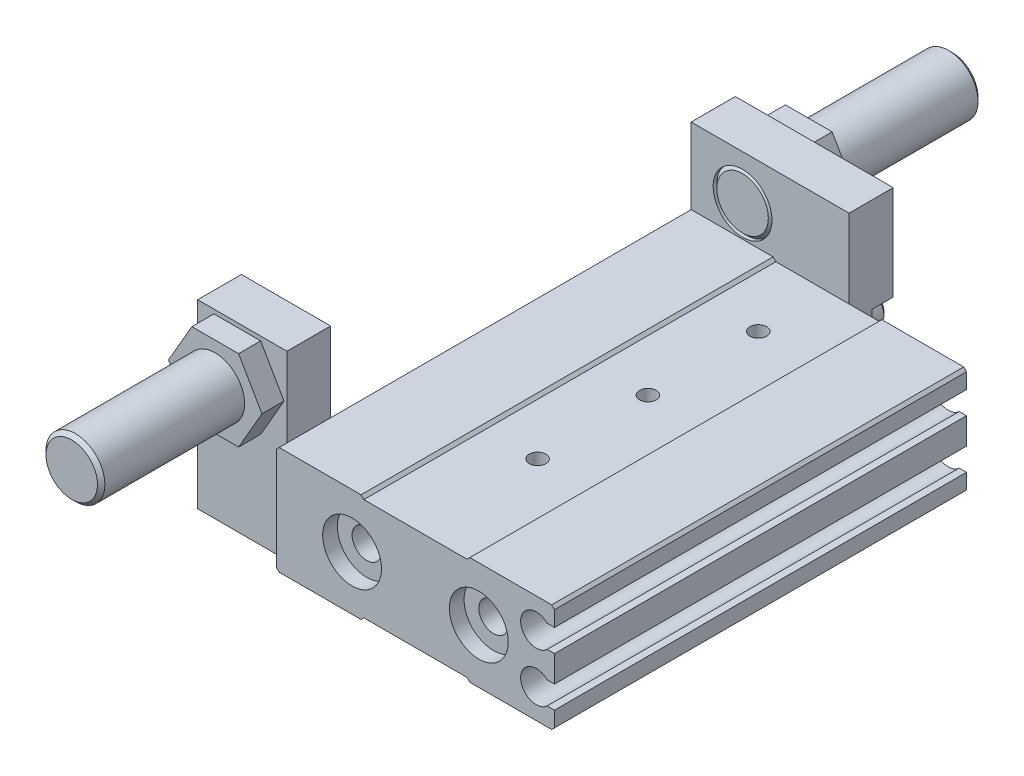
SolidWorks part; units mm, degrees
ref_plane "Front" through (0, 0, 0) normal (0, 0, 1) x (1, 0, 0)
ref_plane "Top" through (0, 0, 0) normal (0, 1, 0) x (1, 0, 0)
ref_plane "Right" through (0, 0, 0) normal (1, 0, 0) x (0, 0, -1)
ref_plane "Plane4" through (0, 0, 0) normal (0, 0, 1) x (-1, 0, 0)
sketch "Sketch1" plane through (0, 0, 57.45) normal (0, 0, 1) x (-1, 0, 0)
  line L0 (18.519, 7.3406) -> (18.9, 6.9596)
  line L1 (-7.0104, 6.9596) -> (7.0104, 6.9596)
  line L2 (18.519, 7.3406) -> (7.3914, 7.3406)
  line L3 (-7.3914, 7.3406) -> (-18.519, 7.3406)
  line L4 (7.0104, 6.9596) -> (7.3914, 7.3406)
  line L5 (-7.0104, 6.9596) -> (-7.3914, 7.3406)
  line L6 (-18.9, 6.9596) -> (-18.9, 4.8641)
  line L7 (-18.9, -6.9596) -> (-18.519, -7.3406)
  line L8 (-7.0104, -6.9596) -> (-7.3914, -7.3406)
  line L9 (-18.9, 1.7907) -> (-18.9, -1.7907)
  line L10 (-18.9, -4.8641) -> (-18.9, -6.9596)
  line L11 (-18.9, 6.9596) -> (-18.519, 7.3406)
  line L12 (18.9, 6.9596) -> (18.9, -6.9596)
  line L14 (-50, 0) -> (50, 0) construction
  line L15 (-7.3914, -7.3406) -> (-18.519, -7.3406)
  line L16 (-17.9137, -4.8641) -> (-18.9, -4.8641)
  line L17 (-14.3, 7.3406) -> (-14.3, 3.3274) construction
  line L18 (-7.0104, -6.9596) -> (7.0104, -6.9596)
  line L19 (7.0104, -6.9596) -> (7.3914, -7.3406)
  line L20 (18.9, -6.9596) -> (18.519, -7.3406)
  line L22 (-18.9, 0) -> (18.9, 0) construction
  line L23 (0, 0) -> (0, 6.9596) construction
  line L26 (18.519, -7.3406) -> (7.3914, -7.3406)
  line L27 (-17.9137, -1.7907) -> (-18.9, -1.7907)
  line L28 (-17.9137, 1.7907) -> (-18.9, 1.7907)
  line L29 (-17.9137, 4.8641) -> (-18.9, 4.8641)
  arc A0 (-17.9137, 1.7907) -> (-17.9137, 4.8641) centre (-16.4336, 3.3274) ccw
  arc A1 (-17.9137, -4.8641) -> (-17.9137, -1.7907) centre (-16.4336, -3.3274) ccw
  dimension "D5" = 4.2672
  dimension "D1" = 14.6812
  dimension "D2" = 45
  dimension "D3" = 0.381
  dimension "D4" = 4.6
  dimension "D6" = 14.0208
  dimension "D7" = 6.6548
  dimension "D8" = 3.0734
extrude "Base-Extrude" add sketch "Sketch1" along normal up to surface (56 mm away)
ref_plane "Plane8" through (0, 0, 55.45) normal (0, 0, 1) x (1, 0, 0)
sketch "Sketch2" plane through (0, 0, 57.45) normal (0, 0, -1) x (-1, 0, 0)
  line L0 (28.0615, 0) -> (-28.0615, 0) construction
  line L5 (0, 6.9596) -> (0, -6.9596) construction
  line L6 (7.0104, 6.9596) -> (-7.0104, 6.9596) construction
  line L7 (-7.0104, -6.9596) -> (7.0104, -6.9596) construction
  circle A0 centre (-8.6106, 0) radius 4
  circle A1 centre (8.6106, 0) radius 4
  dimension "D1" = 8
  dimension "D2" = 17.2212
extrude "Cut-Extrude1" cut sketch "Sketch2" along normal up to surface (54.7 mm away)
sketch "Sketch4" plane through (0, 0, 55.45) normal (0, 0, 1) x (1, 0, 0)
  circle A2 centre (8.6106, 0) radius 4 construction
  circle A3 centre (-8.6106, 0) radius 4 construction
  circle A4 centre (8.6106, 0) radius 4
  circle A5 centre (-8.6106, 0) radius 4
extrude "Boss-Extrude1" add sketch "Sketch4" against normal blind 10
sketch "Sketch19" plane through (0, 0, 55.45) normal (0, 0, 1) x (1, 0, 0)
  circle A0 centre (8.6106, 0) radius 2
  circle A1 centre (-8.6106, 0) radius 2
  circle A2 centre (-8.6106, 0) radius 4 construction
  circle A3 centre (8.6106, 0) radius 4 construction
  dimension "D1" = 4
extrude "Cut-Extrude3" cut sketch "Sketch19" against normal up to next
hole_wizard "#4-40 Tapped Hole2" positions "Sketch21" profile "Sketch20" tap size "#4-40" standard "Ansi Inch" end condition through all
sketch "Sketch21" plane through (0, -6.9596, 0) normal (0, -1, 0) x (1, 0, 0)
  point P0 (0, 40.85)
  point P1 (0, 25.85)
  point P2 (0, 10.85)
sketch "Sketch20" plane through (0, -6.9596, 40.85) normal (1, 0, 0) x (0, 0, -1)
  line L0 (0, 0) -> (0, 14.3002)
  line L1 (0, 14.3002) -> (1.1303, 14.3002)
  line L3 (1.1303, 14.3002) -> (1.1303, 5.6896)
  line L4 (1.1303, 5.6896) -> (1.4224, 5.6896)
  line L5 (1.4224, 5.6896) -> (1.4224, 0)
  line L7 (1.4224, 0) -> (0, 0)
  line L11 (0, -6.35) -> (0, 107.95) construction
  dimension "Thru Tap Drill Dia." = 2.2606
  dimension "Thru Tap Drill Depth" = 14.3002
  dimension "Thread Major Dia." = 2.8448
  dimension "Thread Depth" = 5.6896
hole_wizard "#3-48 Tapped Hole1" positions "Sketch23" profile "Sketch22" tap size "#3-56" standard "Ansi Inch"
sketch "Sketch23" plane through (0, 0, 1.45) normal (0, 0, -1) x (-1, 0, 0)
  line L0 (7.3914, -7.3406) -> (18.519, -7.3406) construction
  point P0 (16, -4.6406)
  point P1 (16, 4.3594)
  point P2 (-0.002, -4.6406)
  point P3 (-0.002, 2.3594)
  dimension "D1" = 2.7
  dimension "D2" = 9
  dimension "D3" = 16.002
  dimension "D4" = 16
  dimension "D5" = 7
sketch "Sketch22" plane through (-16, -4.6406, 1.45) normal (1, 0, 0) x (0, 1, 0)
  line L0 (0, 0) -> (0, 7.9282)
  line L1 (0, 7.9282) -> (1.0414, 7.3025)
  line L2 (1.0414, 7.3025) -> (1.0414, 5.0292)
  line L3 (1.0414, 5.0292) -> (1.2573, 5.0292)
  line L4 (1.2573, 5.0292) -> (1.2573, 0)
  line L5 (1.2573, 0) -> (0, 0)
  line L10 (0, 7.9282) -> (-1.0414, 7.3025) construction
  line L11 (0, -6.35) -> (0, 107.95) construction
  dimension "Tap Drill Dia." = 2.0828
  dimension "Tap Drill Depth" = 7.3025
  dimension "Thread Dia." = 2.5146
  dimension "Thread Depth" = 5.0292
  dimension "Drill Angle" = 118
hole_wizard "Hole1" positions "Sketch25" profile "Sketch24" legacy
sketch "Sketch25" plane through (0, -7.3406, 0) normal (0, -1, 0) x (1, 0, 0)
  point P0 (-14, 42.15)
sketch "Sketch24" plane through (-14, -7.3406, 42.15) normal (1, 0, 0) x (0, 0, -1)
  line L0 (0, 0) -> (0, 2.54)
  line L1 (0, 2.54) -> (1.5939, 2.54)
  line L2 (1.5939, 2.54) -> (1.5939, 0)
  line L3 (1.5939, 0) -> (0, 0)
  line L4 (0, 110) -> (0, -10) construction
  dimension "Diameter" = 3.1877
  dimension "Depth" = 2.54
sketch "Sketch27" plane through (0, -7.3406, 0) normal (0, -1, 0) x (1, 0, 0)
  line L0 (-18.9, 14.15) -> (-14, 14.15) construction
  line L1 (-18.9, 57.45) -> (-18.9, 1.45) construction
  line L2 (-18.9, 16.15) -> (-14, 16.15) construction
  line L3 (-18.9, 12.15) -> (-14, 12.15) construction
  line L4 (-15.5938, 14.5561) -> (-15.5938, 13.7438)
  line L5 (-12.4062, 14.5561) -> (-12.4062, 13.7438)
  arc A0 (-15.5938, 13.7438) -> (-12.4062, 13.7438) centre (-14, 13.7438) ccw
  arc A1 (-12.4062, 14.5561) -> (-15.5938, 14.5561) centre (-14, 14.5561) ccw
  dimension "D1" = 3.1877
  dimension "D2" = 4
extrude "Cut-Extrude4" cut sketch "Sketch27" against normal blind 2.5
hole_wizard "#10-32 Tapped Hole1" positions "Sketch29" profile "Sketch28" tap size "#10-32" standard "Ansi Inch"
sketch "Sketch29" plane through (-18.9, 0, 0) normal (-1, 0, 0) x (0, 0, 1)
  line L0 (57.45, 6.9596) -> (57.45, -6.9596) construction
  line L3 (1.45, -7.3406) -> (57.45, -7.3406) construction
  point P0 (44.95, -0.1406)
  dimension "D1" = 12.5
  dimension "D2" = 7.2
sketch "Sketch28" plane through (-18.9, -0.1406, 44.95) normal (0, 1, 0) x (0, 0, 1)
  line L0 (0, 0) -> (0, 13.2427)
  line L1 (0, 13.2427) -> (2.0193, 12.0294)
  line L2 (2.0193, 12.0294) -> (2.0193, 9.652)
  line L3 (2.0193, 9.652) -> (2.413, 9.652)
  line L4 (2.413, 9.652) -> (2.413, 0)
  line L5 (2.413, 0) -> (0, 0)
  line L10 (0, 13.2427) -> (-2.0193, 12.0294) construction
  line L11 (0, -6.35) -> (0, 107.95) construction
  dimension "Tap Drill Dia." = 4.0386
  dimension "Tap Drill Depth" = 12.0294
  dimension "Thread Major Dia." = 4.826
  dimension "Thread Depth" = 9.652
  dimension "Drill Angle" = 118
sketch "Sketch30" plane through (0, 0, 1.45) normal (0, 0, -1) x (-1, 0, 0)
  line L0 (-7.0104, -6.9596) -> (7.0104, -6.9596) construction
  line L1 (-2.941, 17.6514) -> (18.519, 17.6514)
  line L2 (-2.941, 17.6514) -> (-2.941, -6.5786)
  line L3 (-2.941, -6.5786) -> (18.519, -6.5786)
  line L4 (18.519, 17.6514) -> (18.519, -6.5786)
  line L5 (18.9, -6.9596) -> (18.9, 6.9596) construction
  dimension "D1" = 0.381
  dimension "D2" = 0.381
  dimension "D3" = 24.23
  dimension "D4" = 21.46
extrude "Boss-Extrude2" add sketch "Sketch30" along normal blind 6
sketch "Sketch31" plane through (0, 0, -4.55) normal (0, 0, -1) x (-1, 0, 0)
  line L0 (17.8899, 11.5714) -> (14.7144, 17.0714)
  line L1 (14.7144, 17.0714) -> (8.3636, 17.0714)
  line L2 (8.3636, 17.0714) -> (5.1881, 11.5714)
  line L3 (5.1881, 11.5714) -> (8.3636, 6.0714)
  line L4 (8.3636, 6.0714) -> (14.7144, 6.0714)
  line L5 (14.7144, 6.0714) -> (17.8899, 11.5714)
  line L6 (18.519, 17.6514) -> (-2.941, 17.6514) construction
  line L7 (18.519, -6.5786) -> (18.519, 17.6514) construction
  circle A0 centre (11.539, 11.5714) radius 6.3509 construction
  dimension "D1" = 6.08
  dimension "D2" = 6.98
  dimension "D3" = 11
sketch "Sketch48" plane through (0, 0, -4.55) normal (0, 0, -1) x (-1, 0, 0)
  line L0 (16, 6.7744) -> (18.519, 6.7744)
  line L1 (18.519, 6.7744) -> (18.519, 1.9444)
  line L2 (18.519, -6.5786) -> (18.519, 17.6514) construction
  line L3 (16, 1.9444) -> (18.519, 1.9444)
  line L4 (2.413, -4.6406) -> (2.413, -6.5786)
  line L5 (-2.941, -6.5786) -> (18.519, -6.5786) construction
  line L6 (2.413, -6.5786) -> (-2.941, -6.5786)
  line L7 (-0.002, -2.2256) -> (-2.941, -2.2256)
  line L8 (-2.941, 17.6514) -> (-2.941, -6.5786) construction
  line L9 (-2.941, -2.2256) -> (-2.941, -6.5786)
  line L10 (16, -2.2256) -> (18.519, -2.2256)
  line L11 (18.519, -2.2256) -> (18.519, -6.5786)
  line L12 (13.585, -4.6406) -> (13.585, -6.5786)
  line L13 (13.585, -6.5786) -> (18.519, -6.5786)
  line L14 (-0.002, 4.7744) -> (-2.941, 4.7744)
  line L15 (-0.002, -0.0556) -> (-2.941, -0.0556)
  line L16 (-2.941, -0.0556) -> (-2.941, 4.7744)
  arc A0 (16, 6.7744) -> (16, 1.9444) centre (16, 4.3594) ccw
  arc A1 (2.413, -4.6406) -> (-0.002, -2.2256) centre (-0.002, -4.6406) ccw
  arc A2 (16, -2.2256) -> (13.585, -4.6406) centre (16, -4.6406) ccw
  arc A3 (-0.002, -0.0556) -> (-0.002, 4.7744) centre (-0.002, 2.3594) ccw
  dimension "D1" = 2.415
extrude "Cut-Extrude9" cut sketch "Sketch48" against normal blind 2.87
extrude "Boss-Extrude3" add sketch "Sketch31" along normal blind 3
sketch "Sketch35" plane through (0, 0, -1.68) normal (0, 0, -1) x (-1, 0, 0)
  circle A0 centre (16, 4.3594) radius 2.032
  circle A1 centre (-0.002, 2.3594) radius 2.032
  circle A2 centre (-0.002, -4.6406) radius 2.032
  circle A3 centre (16, -4.6406) radius 2.032
  circle A4 centre (16, -4.6406) radius 1.2573 construction
  circle A7 centre (-0.002, 2.3594) radius 1.2573 construction
  circle A8 centre (-0.002, -4.6406) radius 1.2573 construction
  circle A9 centre (16, 4.3594) radius 1.2573 construction
  dimension "D1" = 4.064
extrude "Boss-Extrude5" add sketch "Sketch35" along normal blind 3
ref_plane "Plane9" through (0, 0, 49.95) normal (0, 0, 1) x (1, 0, 0)
sketch "Sketch36" plane through (0, 0, 49.95) normal (0, 0, 1) x (1, 0, 0)
  line L0 (-19.027, 17.6394) -> (-19.027, 5.3406)
  line L1 (-31.15, 17.6394) -> (-19.027, 17.6394)
  line L2 (-31.15, 17.6394) -> (-31.15, -6.9706)
  line L3 (-31.15, -6.9706) -> (-18.9, -6.9706)
  line L4 (-18.9, 5.3406) -> (-18.9, -6.9706)
  line L5 (-19.027, 5.3406) -> (-18.9, 5.3406)
  line L7 (-18.9, 17.6094) -> (-18.9, -5.8406) construction
  line L8 (-18.519, -7.3406) -> (-7.3914, -7.3406) construction
  line L11 (18.9, 7.3406) -> (-18.9, 7.3406) construction
  dimension "D1" = 12.25
  dimension "D2" = 0.127
  dimension "D3" = 24.61
  dimension "D4" = 0.37
  dimension "D5" = 2
extrude "Boss-Extrude6" add sketch "Sketch36" along normal blind 5.94
sketch "Sketch37" plane through (0, 0, 55.89) normal (0, 0, 1) x (1, 0, 0)
  line L0 (-31.15, 17.6394) -> (-31.15, -6.9706) construction
  line L1 (-22.5946, 17.0714) -> (-28.9454, 17.0714)
  line L2 (-28.9454, 17.0714) -> (-32.1209, 11.5714)
  line L3 (-32.1209, 11.5714) -> (-28.9454, 6.0714)
  line L4 (-28.9454, 6.0714) -> (-22.5946, 6.0714)
  line L5 (-22.5946, 6.0714) -> (-19.4191, 11.5714)
  line L6 (-8.3636, 6.0714) -> (-14.2967, 6.0714) construction
  line L8 (-19.4191, 11.5714) -> (-22.5946, 17.0714)
  circle A0 centre (-25.77, 11.5714) radius 5.5 construction
  dimension "D1" = 5.38
  dimension "D3" = 11
extrude "Boss-Extrude7" add sketch "Sketch37" along normal blind 3
sketch "Sketch38" plane through (0, 0, 58.89) normal (0, 0, 1) x (1, 0, 0)
  line L0 (-19.4191, 11.5714) -> (-22.5946, 17.0714) construction
  line L1 (-32.1209, 11.5714) -> (-28.9454, 6.0714) construction
  line L2 (-22.5946, 17.0714) -> (-28.9454, 17.0714) construction
  circle A0 centre (-25.77, 11.5714) radius 5.5 construction
  circle A1 centre (-25.77, 11.5714) radius 4
  dimension "D1" = 8
ref_plane "Plane11" through (0, 11.5714, 0) normal (0, 1, 0) x (-1, 0, 0)
extrude "Cut-Extrude7" cut sketch "Sketch38" against normal up to next
sketch "Sketch44" plane through (0, 11.5714, 0) normal (0, 1, 0) x (-1, 0, 0)
  line L0 (25.77, 58.89) -> (25.77, 49.95) construction
  line L1 (22.5946, 58.89) -> (28.9454, 58.89) construction
  line L2 (9.7125, 49.95) -> (-9.7125, 49.95) construction
  line L4 (25.77, 78.39) -> (29.77, 78.39)
  line L5 (25.77, 78.39) -> (25.77, 49.95)
  line L6 (25.77, 49.95) -> (29.27, 49.95)
  line L7 (29.77, 78.39) -> (29.77, 50.45)
  line L8 (29.77, 50.45) -> (29.27, 49.95)
  line L10 (29.77, 49.95) -> (29.77, 58.89) construction
  line L11 (19.027, 49.95) -> (31.15, 49.95) construction
  line L12 (19.027, 55.89) -> (31.15, 55.89) construction
  dimension "D1" = 22.5
  dimension "D2" = 45
  dimension "D3" = 0.5
revolve "Boss-Revolve1" add sketch "Sketch44" angle 360 about L0
sketch "Sketch46" plane through (0, 0, -7.55) normal (0, 0, -1) x (-1, 0, 0)
  line L0 (17.8899, 11.5714) -> (14.7144, 17.0714) construction
  line L1 (8.3636, 6.0714) -> (14.7144, 6.0714) construction
  line L2 (8.3636, 17.0714) -> (5.1881, 11.5714) construction
  circle A0 centre (11.539, 11.5714) radius 5.5 construction
  circle A1 centre (11.539, 11.5714) radius 4
  dimension "D1" = 8
extrude "Cut-Extrude8" cut sketch "Sketch46" against normal up to next
ref_plane "Plane12" through (0, 11.5714, 0) normal (0, 1, 0) x (-1, 0, 0)
sketch "Sketch47" plane through (0, 11.5714, 0) normal (0, 1, 0) x (-1, 0, 0)
  line L0 (18.519, 1.45) -> (-2.941, 1.45) construction
  line L2 (15.539, -7.55) -> (15.539, 1.45) construction
  line L3 (15.039, 1.45) -> (11.539, 1.45)
  line L4 (11.539, 1.45) -> (11.539, -27.05)
  line L5 (15.539, -27.05) -> (15.539, 0.95)
  line L6 (11.539, 1.45) -> (11.539, -27.05) construction
  line L7 (11.539, -27.05) -> (15.539, -27.05)
  line L8 (15.539, 0.95) -> (15.039, 1.45)
  line L9 (18.519, -4.55) -> (-2.941, -4.55) construction
  line L10 (11.539, 1.45) -> (11.539, -7.55) construction
  dimension "D1" = 45
  dimension "D2" = 0.5
  dimension "D3" = 22.5
revolve "Boss-Revolve2" add sketch "Sketch47" angle 360 about L6
chamfer "Chamfer3" distance 0.5 angle 45 2 edges at (-7.539, 11.5714, -27.05) (-21.77, 11.5714, 78.39)
chamfer "Chamfer4" distance 0.5 angle 45 4 edges at (-2.03, -4.6406, -4.68) (-2.03, 2.3594, -4.68) (-18.032, 4.3594, -4.68) (-18.032, -4.6406, -4.68)
